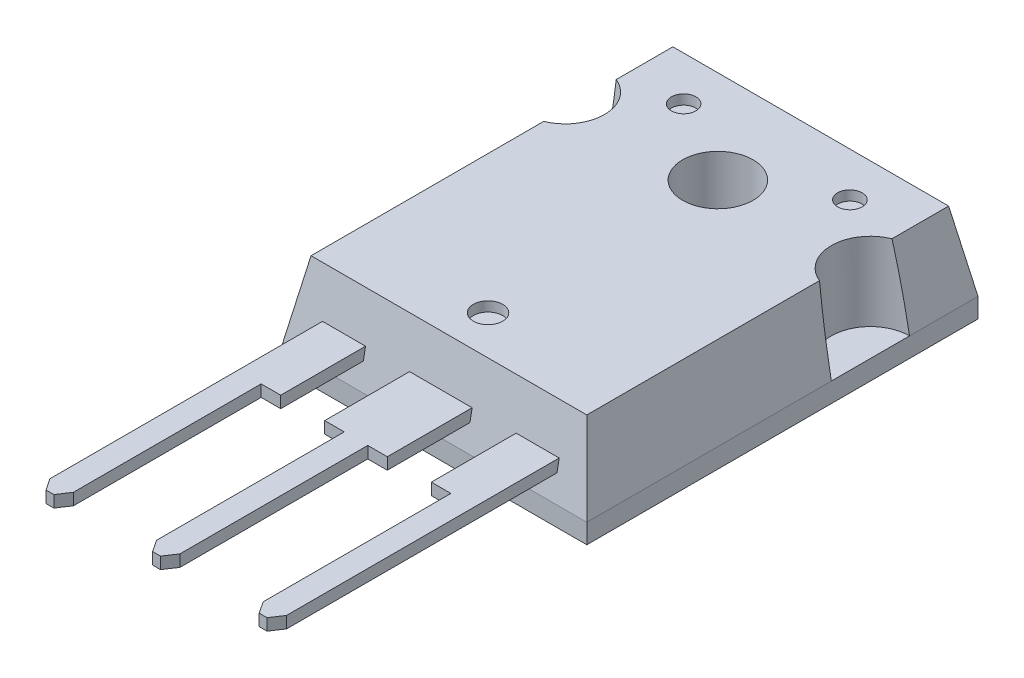
SolidWorks part; units mm, degrees
ref_plane "Front Plane" through (0, 0, 0) normal (0, 0, 1) x (1, 0, 0)
ref_plane "Top Plane" through (0, 0, 0) normal (0, 1, 0) x (1, 0, 0)
ref_plane "Right Plane" through (0, 0, 0) normal (1, 0, 0) x (0, 0, -1)
sketch "Sketch1" plane through (0, 0, 0) normal (0, 0, 1) x (1, 0, 0)
  line L0 (-7.8, 0) -> (7.8, 0) construction
  line L1 (-7.8, -2.5) -> (7.8, -2.5)
  line L2 (-7.8, -2.5) -> (-7.8, 2.5)
  line L3 (-7.8, 2.5) -> (7.8, 2.5)
  line L4 (7.8, -2.5) -> (7.8, 2.5)
  line L5 (0, 2.5) -> (0, -2.5) construction
  point P8 (0, 0)
  dimension "D1" = 15.6
  dimension "D2" = 5
extrude "Boss-Extrude1" add sketch "Sketch1" along normal blind 20
chamfer "Chamfer1" distance 4 distance2 0.75 4 edges at (0, 2.5, 20) (-7.8, 2.5, 10) (0, 2.5, 0) (7.8, 2.5, 10)
sketch "Sketch2" plane through (0, 2.5, 0) normal (0, 1, 0) x (1, 0, 0)
  circle A0 centre (0, -5.5) radius 1.8
  dimension "D1" = 3.6
extrude "Cut-Extrude1" cut sketch "Sketch2" against normal through all
sketch "Sketch3" plane through (0, 2.5, 0) normal (0, 1, 0) x (1, 0, 0)
  line L0 (-7.8, -20) -> (-7.8, 0) construction
  line L1 (7.8, -20) -> (7.8, 0) construction
  circle A0 centre (-7.8, -5.5) radius 2
  circle A1 centre (7.8, -5.5) radius 2
  point P0 (0, -5.5)
extrude "Cut-Extrude2" cut sketch "Sketch3" against normal blind 4
sketch "Sketch4" plane through (0, 2.5, 0) normal (0, 1, 0) x (1, 0, 0)
  line L0 (0, 0) -> (0, -3.7) construction
  line L1 (-7.8, 0) -> (7.8, 0) construction
  circle A0 centre (0, -5.5) radius 1.8 construction
  circle A1 centre (4.25, -3) radius 0.625
  circle A2 centre (-4.25, -3) radius 0.625
  dimension "D3" = 1.25
  dimension "D1" = 4.25
  dimension "D2" = 3
extrude "Cut-Extrude3" cut sketch "Sketch4" against normal blind 0.5
sketch "Sketch5" plane through (0, 2.5, 0) normal (0, 1, 0) x (1, 0, 0)
  line L0 (-7.05, -19.25) -> (7.05, -19.25) construction
  circle A0 centre (0, -17.25) radius 0.75
  dimension "D1" = 2
extrude "Cut-Extrude4" cut sketch "Sketch5" against normal blind 0.5
ref_plane "Plane1" through (0, 0, 0) normal (0, -1, 0) x (-1, 0, 0)
sketch "Sketch6" plane through (0, 0, 0) normal (0, -1, 0) x (-1, 0, 0)
  line L0 (7.8, -20) -> (-7.8, -20) construction
  line L1 (7.8, -20) -> (6.05, -20)
  line L2 (0, -24) -> (0, -40.4202) construction
  line L3 (-6.05, -24) -> (-6.05, -34.2)
  line L4 (6.05, -20) -> (6.05, -24)
  line L5 (6.05, -24) -> (3.85, -24)
  line L6 (-6.05, -20) -> (-6.05, -24)
  line L7 (6.05, -24) -> (4.85, -24)
  line L8 (6.05, -24) -> (6.05, -34.2)
  line L9 (6.05, -34.2) -> (4.85, -34.2)
  line L10 (4.85, -24) -> (4.85, -34.2)
  line L11 (6.05, -33.6) -> (5.65, -34.2)
  line L12 (0, -24) -> (0.6, -24)
  line L13 (0, -24) -> (0, -34.2)
  line L14 (-0.6, -34.2) -> (0.6, -34.2)
  line L15 (0.6, -24) -> (0.6, -34.2)
  line L16 (4.85, -33.6) -> (5.25, -34.2)
  line L17 (0.6, -33.6) -> (0.2, -34.2)
  line L18 (3.85, -24) -> (3.85, -20)
  line L19 (7.05, -19.25) -> (-7.05, -19.25) construction
  line L20 (7.05, -19.25) -> (-7.05, -19.25)
  line L21 (6.05, -20) -> (6.05, -19.25)
  line L22 (3.85, -20) -> (3.85, -19.25)
  line L23 (1.6, -19.25) -> (1.6, -24)
  line L24 (1.6, -24) -> (-6.05, -24)
  line L25 (-6.05, -20) -> (-7.8, -20)
  line L26 (-1.6, -19.25) -> (-1.6, -24)
  line L27 (-1.6, -24) -> (6.05, -24)
  line L28 (-0.6, -33.6) -> (-0.2, -34.2)
  line L29 (-0.6, -24) -> (-0.6, -34.2)
  line L30 (-6.05, -33.6) -> (-5.65, -34.2)
  line L31 (-6.05, -34.2) -> (-4.85, -34.2)
  line L32 (-4.85, -33.6) -> (-5.25, -34.2)
  line L33 (-4.85, -24) -> (-4.85, -34.2)
  line L34 (-3.85, -24) -> (-3.85, -20)
  line L35 (-3.85, -20) -> (-3.85, -19.25)
  line L36 (-6.05, -20) -> (-6.05, -19.25)
  line L37 (-6.05, -20) -> (-6.05, -24)
  point P6 (0, -24)
  dimension "D1" = 4
  dimension "D2" = 12.1
  dimension "D3" = 14.2
  dimension "D4" = 1.2
  dimension "D5" = 0.6
  dimension "D6" = 0.6
  dimension "D7" = 0.6
  dimension "D8" = 0.4
  dimension "D9" = 0.4
  dimension "D10" = 0.6
  dimension "D11" = 0.4
  dimension "D12" = 2.2
  dimension "D13" = 1.6
extrude "Boss-Extrude2" add sketch "Sketch6" along normal blind 0.3 and the other way blind 0.3 contours L10 L16 L9 L11 L8 L5 | L22 L18 L5 L4 L21 L20 | L20 L26 L27 L24 L12 L23 | L36 L6 L24 L34 L35 L20 | L17 L15 L12 L13 L14 | L24 L29 L28 L14 L13 | L33 L24 L3 L30 L31 L32
